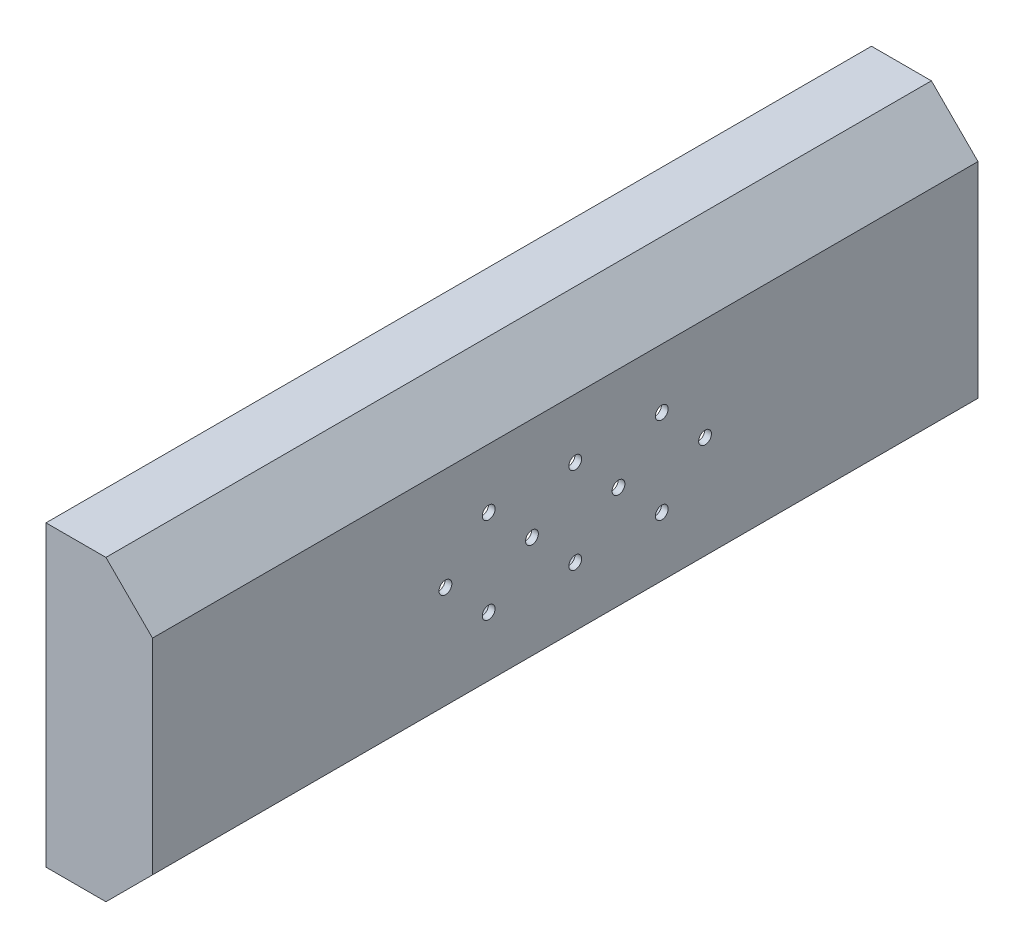
SolidWorks part; units mm, degrees
ref_plane "Front Plane" through (0, 0, 0) normal (0, 0, 1) x (1, 0, 0)
ref_plane "Top Plane" through (0, 0, 0) normal (0, 1, 0) x (1, 0, 0)
ref_plane "Right Plane" through (0, 0, 0) normal (1, 0, 0) x (0, 0, -1)
sketch "Sketch1" plane through (0, 0, 0) normal (0, 1, 0) x (1, 0, 0)
  line L1 (0, 0) -> (20.32, 0)
  line L2 (0, 0) -> (0, 157.48)
  line L3 (0, 157.48) -> (20.32, 157.48)
  line L4 (20.32, 0) -> (20.32, 157.48)
  dimension "D1" = 157.48
  dimension "D2" = 20.32
extrude "Boss-Extrude1" add sketch "Sketch1" along normal blind 56.896
chamfer "Chamfer1" distance 8.89 angle 45 2 edges at (20.32, 56.896, -78.74) (20.32, 0, -78.74)
shell "Shell1" thickness 1.27
hole_wizard "#2 Clearance Hole1" positions "Sketch3" profile "Sketch2" hole size "#2" standard "ANSI Inch"
sketch "Sketch3" plane through (20.32, 0, 0) normal (1, 0, 0) x (0, 0, -1)
  line L0 (157.48, 0) -> (0, 0) construction
  line L1 (0, 48.006) -> (0, 8.89) construction
  point P0 (55.88, 28.448)
  point P2 (72.39, 28.448)
  point P9 (80.645, 36.703)
  point P11 (80.645, 20.193)
  point P13 (88.9, 28.448)
  point P15 (105.41, 28.448)
  point P17 (97.155, 36.703)
  point P19 (97.155, 20.193)
  point P21 (64.135, 36.703)
  point P23 (64.135, 20.193)
  dimension "D1" = 28.448
  dimension "D2" = 16.51
  dimension "D3" = 55.88
  dimension "D4" = 28.448
  dimension "D5" = 16.51
  dimension "D6" = 16.51
  dimension "D7" = 16.51
  dimension "D8" = 16.51
  dimension "D9" = 16.51
  dimension "D10" = 8.255
  dimension "D11" = 16.51
  dimension "D12" = 16.51
  dimension "D13" = 16.51
  dimension "D14" = 16.51
  dimension "D15" = 8.255
  dimension "D16" = 8.255
sketch "Sketch2" plane through (20.32, 28.448, -55.88) normal (0, 1, 0) x (0, 0, -1)
  line L0 (0, 0) -> (0, 8.3526)
  line L1 (0, 8.3526) -> (1.2192, 7.62)
  line L2 (1.2192, 7.62) -> (1.2192, 0)
  line L5 (1.2192, 0) -> (0, 0)
  line L10 (0, 8.3526) -> (-1.2192, 7.62) construction
  line L11 (0, -6.35) -> (0, 107.95) construction
  dimension "Hole Dia." = 2.4384
  dimension "Hole Depth" = 7.62
  dimension "Drill Angle" = 118
